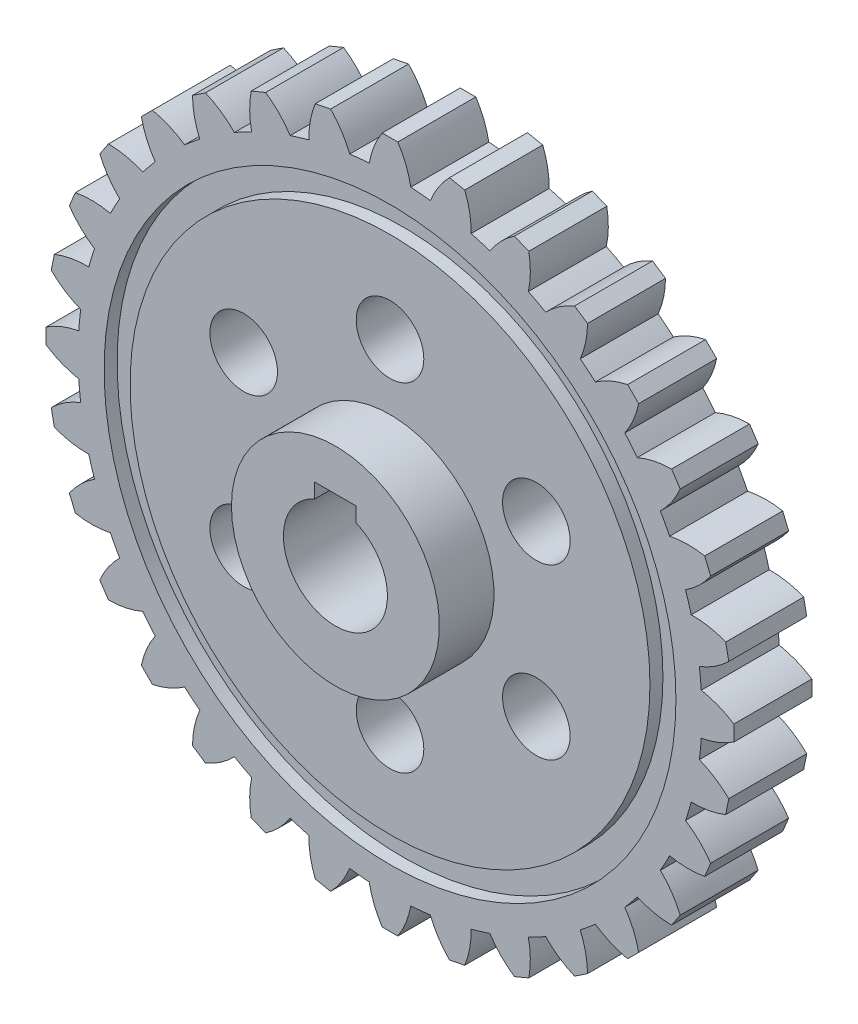
SolidWorks part; units mm, degrees
ref_plane "Front Plane" through (0, 0, 0) normal (0, 0, 1) x (1, 0, 0)
ref_plane "Top Plane" through (0, 0, 0) normal (0, 1, 0) x (1, 0, 0)
ref_plane "Right Plane" through (0, 0, 0) normal (1, 0, 0) x (0, 0, -1)
sketch "Sketch1" plane through (0, 0, 0) normal (0, 0, 1) x (1, 0, 0)
  circle A0 centre (0, 0) radius 60
  dimension "D1" = 120
extrude "Boss-Extrude1" add sketch "Sketch1" along normal blind 15
sketch "Sketch2" plane through (0, 0, 15) normal (0, 0, 1) x (1, 0, 0)
  line L0 (0, 40.3685) -> (0, -38.6295) construction
  circle A0 centre (0, 0) radius 32.5 construction
  circle A1 centre (0, 32.5) radius 6.5
  circle A2 centre (28.1458, 16.25) radius 6.5
  circle A3 centre (28.1458, -16.25) radius 6.5
  circle A4 centre (0, -32.5) radius 6.5
  circle A5 centre (-28.1458, -16.25) radius 6.5
  circle A6 centre (-28.1458, 16.25) radius 6.5
  point P19 (0, 0)
  dimension "D1" = 65
  dimension "D2" = 13
  dimension "D3" = 6
extrude "Cut-Extrude1" cut sketch "Sketch2" against normal through all
sketch "Sketch3" plane through (0, 0, 15) normal (0, 0, 1) x (1, 0, 0)
  circle A0 centre (0, 0) radius 20
  dimension "D1" = 40
extrude "Boss-Extrude2" add sketch "Sketch3" along normal blind 10.5
sketch "Sketch4" plane through (0, 0, 25.5) normal (0, 0, 1) x (1, 0, 0)
  line L1 (-4, 12) -> (4, 12)
  line L2 (-4, 12) -> (-4, 9.1652)
  line L4 (4, 12) -> (4, 9.1652)
  arc A0 (-4, 9.1652) -> (4, 9.1652) centre (0, 0) ccw
  dimension "D1" = 20
  dimension "D2" = 12
  dimension "D3" = 8
  dimension "D4" = 4
extrude "Cut-Extrude2" cut sketch "Sketch4" against normal through all
sketch "Sketch5" plane through (0, 0, 15) normal (0, 0, 1) x (1, 0, 0)
  circle A0 centre (0, 0) radius 55
  circle A1 centre (0, 0) radius 50
  dimension "D1" = 100
  dimension "D2" = 110
extrude "Cut-Extrude3" cut sketch "Sketch5" against normal blind 2.5
ref_plane "Plane1" through (0, 0, 7.5) normal (0, 0, 1) x (1, 0, 0)
mirror "Mirror1" about plane through (0, 0, 7.5) normal (0, 0, 1) of "Cut-Extrude2", "Cut-Extrude3", "Boss-Extrude2"
sketch "Sketch6" plane through (0, 0, 15) normal (0, 0, 1) x (1, 0, 0)
  line L0 (0, 128.5043) -> (0, -108.0951) construction
  line L1 (-1.5, 66.1365) -> (1.5, 66.1365)
  line L2 (11.4314, 65.1584) -> (14.3738, 64.5731)
  line L3 (23.9235, 61.6762) -> (26.6952, 60.5282)
  line L4 (35.4963, 55.8239) -> (37.9907, 54.1571)
  line L5 (45.7049, 47.8262) -> (47.8262, 45.7049)
  line L6 (54.1571, 37.9907) -> (55.8239, 35.4963)
  line L7 (60.5282, 26.6952) -> (61.6762, 23.9235)
  line L8 (64.5731, 14.3738) -> (65.1584, 11.4314)
  line L9 (66.1365, 1.5) -> (66.1365, -1.5)
  line L10 (65.1584, -11.4314) -> (64.5731, -14.3738)
  line L11 (61.6762, -23.9235) -> (60.5282, -26.6952)
  line L12 (55.8239, -35.4963) -> (54.1571, -37.9907)
  line L13 (47.8262, -45.7049) -> (45.7049, -47.8262)
  line L14 (37.9907, -54.1571) -> (35.4963, -55.8239)
  line L15 (26.6952, -60.5282) -> (23.9235, -61.6762)
  line L16 (14.3738, -64.5731) -> (11.4314, -65.1584)
  line L17 (1.5, -66.1365) -> (-1.5, -66.1365)
  line L18 (-11.4314, -65.1584) -> (-14.3738, -64.5731)
  line L19 (-23.9235, -61.6762) -> (-26.6952, -60.5282)
  line L20 (-35.4963, -55.8239) -> (-37.9907, -54.1571)
  line L21 (-45.7049, -47.8262) -> (-47.8262, -45.7049)
  line L22 (-54.1571, -37.9907) -> (-55.8239, -35.4963)
  line L23 (-60.5282, -26.6952) -> (-61.6762, -23.9235)
  line L24 (-64.5731, -14.3738) -> (-65.1584, -11.4314)
  line L25 (-66.1365, -1.5) -> (-66.1365, 1.5)
  line L26 (-65.1584, 11.4314) -> (-64.5731, 14.3738)
  line L27 (-61.6762, 23.9235) -> (-60.5282, 26.6952)
  line L28 (-55.8239, 35.4963) -> (-54.1571, 37.9907)
  line L29 (-47.8262, 45.7049) -> (-45.7049, 47.8262)
  line L30 (-37.9907, 54.1571) -> (-35.4963, 55.8239)
  line L31 (-26.6952, 60.5282) -> (-23.9235, 61.6762)
  line L32 (-14.3738, 64.5731) -> (-11.4314, 65.1584)
  arc A0 (-1.5, 66.1365) -> (-4, 59.8665) centre (12.7267, 56.8306) ccw
  circle A1 centre (0, 0) radius 60 construction
  arc A2 (1.5, 66.1365) -> (4, 59.8665) centre (-12.7267, 56.8306) cw
  arc A3 (4, 59.8665) -> (-4, 59.8665) centre (0, 0) ccw
  arc A4 (14.3738, 64.5731) -> (15.6025, 57.9358) centre (-1.3951, 58.2215) cw
  arc A5 (11.4314, 65.1584) -> (7.7562, 59.4966) centre (23.5693, 53.2557) ccw
  arc A6 (15.6025, 57.9358) -> (7.7562, 59.4966) centre (0, 0) ccw
  arc A7 (26.6952, 60.5282) -> (26.6054, 53.7787) centre (9.9902, 57.3749) cw
  arc A8 (23.9235, 61.6762) -> (19.2144, 56.8402) centre (33.5061, 47.6343) ccw
  arc A9 (26.6054, 53.7787) -> (19.2144, 56.8402) centre (0, 0) ccw
  arc A10 (37.9907, 54.1571) -> (36.5859, 47.5549) centre (20.9915, 54.3235) cw
  arc A11 (35.4963, 55.8239) -> (29.9342, 51.9995) centre (42.1553, 40.1823) ccw
  arc A12 (36.5859, 47.5549) -> (29.9342, 51.9995) centre (0, 0) ccw
  arc A13 (47.8262, 45.7049) -> (45.1604, 39.5036) centre (31.1861, 49.1844) cw
  arc A14 (45.7049, 47.8262) -> (39.5036, 45.1604) centre (49.1844, 31.1861) ccw
  arc A15 (45.1604, 39.5036) -> (39.5036, 45.1604) centre (0, 0) ccw
  arc A16 (55.8239, 35.4963) -> (51.9995, 29.9342) centre (40.1823, 42.1553) cw
  arc A17 (54.1571, 37.9907) -> (47.5549, 36.5859) centre (54.3235, 20.9915) ccw
  arc A18 (51.9995, 29.9342) -> (47.5549, 36.5859) centre (0, 0) ccw
  arc A19 (61.6762, 23.9235) -> (56.8402, 19.2144) centre (47.6343, 33.5061) cw
  arc A20 (60.5282, 26.6952) -> (53.7787, 26.6054) centre (57.3749, 9.9902) ccw
  arc A21 (56.8402, 19.2144) -> (53.7787, 26.6054) centre (0, 0) ccw
  arc A22 (65.1584, 11.4314) -> (59.4966, 7.7562) centre (53.2557, 23.5693) cw
  arc A23 (64.5731, 14.3738) -> (57.9358, 15.6025) centre (58.2215, -1.3951) ccw
  arc A24 (59.4966, 7.7562) -> (57.9358, 15.6025) centre (0, 0) ccw
  arc A25 (66.1365, -1.5) -> (59.8665, -4) centre (56.8306, 12.7267) cw
  arc A26 (66.1365, 1.5) -> (59.8665, 4) centre (56.8306, -12.7267) ccw
  arc A27 (59.8665, -4) -> (59.8665, 4) centre (0, 0) ccw
  arc A28 (64.5731, -14.3738) -> (57.9358, -15.6025) centre (58.2215, 1.3951) cw
  arc A29 (65.1584, -11.4314) -> (59.4966, -7.7562) centre (53.2557, -23.5693) ccw
  arc A30 (57.9358, -15.6025) -> (59.4966, -7.7562) centre (0, 0) ccw
  arc A31 (60.5282, -26.6952) -> (53.7787, -26.6054) centre (57.3749, -9.9902) cw
  arc A32 (61.6762, -23.9235) -> (56.8402, -19.2144) centre (47.6343, -33.5061) ccw
  arc A33 (53.7787, -26.6054) -> (56.8402, -19.2144) centre (0, 0) ccw
  arc A34 (54.1571, -37.9907) -> (47.5549, -36.5859) centre (54.3235, -20.9915) cw
  arc A35 (55.8239, -35.4963) -> (51.9995, -29.9342) centre (40.1823, -42.1553) ccw
  arc A36 (47.5549, -36.5859) -> (51.9995, -29.9342) centre (0, 0) ccw
  arc A37 (45.7049, -47.8262) -> (39.5036, -45.1604) centre (49.1844, -31.1861) cw
  arc A38 (47.8262, -45.7049) -> (45.1604, -39.5036) centre (31.1861, -49.1844) ccw
  arc A39 (39.5036, -45.1604) -> (45.1604, -39.5036) centre (0, 0) ccw
  arc A40 (35.4963, -55.8239) -> (29.9342, -51.9995) centre (42.1553, -40.1823) cw
  arc A41 (37.9907, -54.1571) -> (36.5859, -47.5549) centre (20.9915, -54.3235) ccw
  arc A42 (29.9342, -51.9995) -> (36.5859, -47.5549) centre (0, 0) ccw
  arc A43 (23.9235, -61.6762) -> (19.2144, -56.8402) centre (33.5061, -47.6343) cw
  arc A44 (26.6952, -60.5282) -> (26.6054, -53.7787) centre (9.9902, -57.3749) ccw
  arc A45 (19.2144, -56.8402) -> (26.6054, -53.7787) centre (0, 0) ccw
  arc A46 (11.4314, -65.1584) -> (7.7562, -59.4966) centre (23.5693, -53.2557) cw
  arc A47 (14.3738, -64.5731) -> (15.6025, -57.9358) centre (-1.3951, -58.2215) ccw
  arc A48 (7.7562, -59.4966) -> (15.6025, -57.9358) centre (0, 0) ccw
  arc A49 (-1.5, -66.1365) -> (-4, -59.8665) centre (12.7267, -56.8306) cw
  arc A50 (1.5, -66.1365) -> (4, -59.8665) centre (-12.7267, -56.8306) ccw
  arc A51 (-4, -59.8665) -> (4, -59.8665) centre (0, 0) ccw
  arc A52 (-14.3738, -64.5731) -> (-15.6025, -57.9358) centre (1.3951, -58.2215) cw
  arc A53 (-11.4314, -65.1584) -> (-7.7562, -59.4966) centre (-23.5693, -53.2557) ccw
  arc A54 (-15.6025, -57.9358) -> (-7.7562, -59.4966) centre (0, 0) ccw
  arc A55 (-26.6952, -60.5282) -> (-26.6054, -53.7787) centre (-9.9902, -57.3749) cw
  arc A56 (-23.9235, -61.6762) -> (-19.2144, -56.8402) centre (-33.5061, -47.6343) ccw
  arc A57 (-26.6054, -53.7787) -> (-19.2144, -56.8402) centre (0, 0) ccw
  arc A58 (-37.9907, -54.1571) -> (-36.5859, -47.5549) centre (-20.9915, -54.3235) cw
  arc A59 (-35.4963, -55.8239) -> (-29.9342, -51.9995) centre (-42.1553, -40.1823) ccw
  arc A60 (-36.5859, -47.5549) -> (-29.9342, -51.9995) centre (0, 0) ccw
  arc A61 (-47.8262, -45.7049) -> (-45.1604, -39.5036) centre (-31.1861, -49.1844) cw
  arc A62 (-45.7049, -47.8262) -> (-39.5036, -45.1604) centre (-49.1844, -31.1861) ccw
  arc A63 (-45.1604, -39.5036) -> (-39.5036, -45.1604) centre (0, 0) ccw
  arc A64 (-55.8239, -35.4963) -> (-51.9995, -29.9342) centre (-40.1823, -42.1553) cw
  arc A65 (-54.1571, -37.9907) -> (-47.5549, -36.5859) centre (-54.3235, -20.9915) ccw
  arc A66 (-51.9995, -29.9342) -> (-47.5549, -36.5859) centre (0, 0) ccw
  arc A67 (-61.6762, -23.9235) -> (-56.8402, -19.2144) centre (-47.6343, -33.5061) cw
  arc A68 (-60.5282, -26.6952) -> (-53.7787, -26.6054) centre (-57.3749, -9.9902) ccw
  arc A69 (-56.8402, -19.2144) -> (-53.7787, -26.6054) centre (0, 0) ccw
  arc A70 (-65.1584, -11.4314) -> (-59.4966, -7.7562) centre (-53.2557, -23.5693) cw
  arc A71 (-64.5731, -14.3738) -> (-57.9358, -15.6025) centre (-58.2215, 1.3951) ccw
  arc A72 (-59.4966, -7.7562) -> (-57.9358, -15.6025) centre (0, 0) ccw
  arc A73 (-66.1365, 1.5) -> (-59.8665, 4) centre (-56.8306, -12.7267) cw
  arc A74 (-66.1365, -1.5) -> (-59.8665, -4) centre (-56.8306, 12.7267) ccw
  arc A75 (-59.8665, 4) -> (-59.8665, -4) centre (0, 0) ccw
  arc A76 (-64.5731, 14.3738) -> (-57.9358, 15.6025) centre (-58.2215, -1.3951) cw
  arc A77 (-65.1584, 11.4314) -> (-59.4966, 7.7562) centre (-53.2557, 23.5693) ccw
  arc A78 (-57.9358, 15.6025) -> (-59.4966, 7.7562) centre (0, 0) ccw
  arc A79 (-60.5282, 26.6952) -> (-53.7787, 26.6054) centre (-57.3749, 9.9902) cw
  arc A80 (-61.6762, 23.9235) -> (-56.8402, 19.2144) centre (-47.6343, 33.5061) ccw
  arc A81 (-53.7787, 26.6054) -> (-56.8402, 19.2144) centre (0, 0) ccw
  arc A82 (-54.1571, 37.9907) -> (-47.5549, 36.5859) centre (-54.3235, 20.9915) cw
  arc A83 (-55.8239, 35.4963) -> (-51.9995, 29.9342) centre (-40.1823, 42.1553) ccw
  arc A84 (-47.5549, 36.5859) -> (-51.9995, 29.9342) centre (0, 0) ccw
  arc A85 (-45.7049, 47.8262) -> (-39.5036, 45.1604) centre (-49.1844, 31.1861) cw
  arc A86 (-47.8262, 45.7049) -> (-45.1604, 39.5036) centre (-31.1861, 49.1844) ccw
  arc A87 (-39.5036, 45.1604) -> (-45.1604, 39.5036) centre (0, 0) ccw
  arc A88 (-35.4963, 55.8239) -> (-29.9342, 51.9995) centre (-42.1553, 40.1823) cw
  arc A89 (-37.9907, 54.1571) -> (-36.5859, 47.5549) centre (-20.9915, 54.3235) ccw
  arc A90 (-29.9342, 51.9995) -> (-36.5859, 47.5549) centre (0, 0) ccw
  arc A91 (-23.9235, 61.6762) -> (-19.2144, 56.8402) centre (-33.5061, 47.6343) cw
  arc A92 (-26.6952, 60.5282) -> (-26.6054, 53.7787) centre (-9.9902, 57.3749) ccw
  arc A93 (-19.2144, 56.8402) -> (-26.6054, 53.7787) centre (0, 0) ccw
  arc A94 (-11.4314, 65.1584) -> (-7.7562, 59.4966) centre (-23.5693, 53.2557) cw
  arc A95 (-14.3738, 64.5731) -> (-15.6025, 57.9358) centre (1.3951, 58.2215) ccw
  arc A96 (-7.7562, 59.4966) -> (-15.6025, 57.9358) centre (0, 0) ccw
  point P5 (0, 66.1365)
  point P202 (0, 0)
  dimension "D1" = 3
  dimension "D4" = 17
  dimension "D5" = 17
  dimension "D7" = 32
  dimension "D2" = 8
  dimension "D3" = 4
  dimension "D6" = 6.27
extrude "Boss-Extrude3" add sketch "Sketch6" against normal up to surface (15 mm away) up to face at (55, 0, 0)
sketch "Sketch7" plane through (0, 0, 15) normal (0, 0, 1) x (1, 0, 0)
  circle A0 centre (0, 0) radius 66.5
  dimension "D1" = 133
